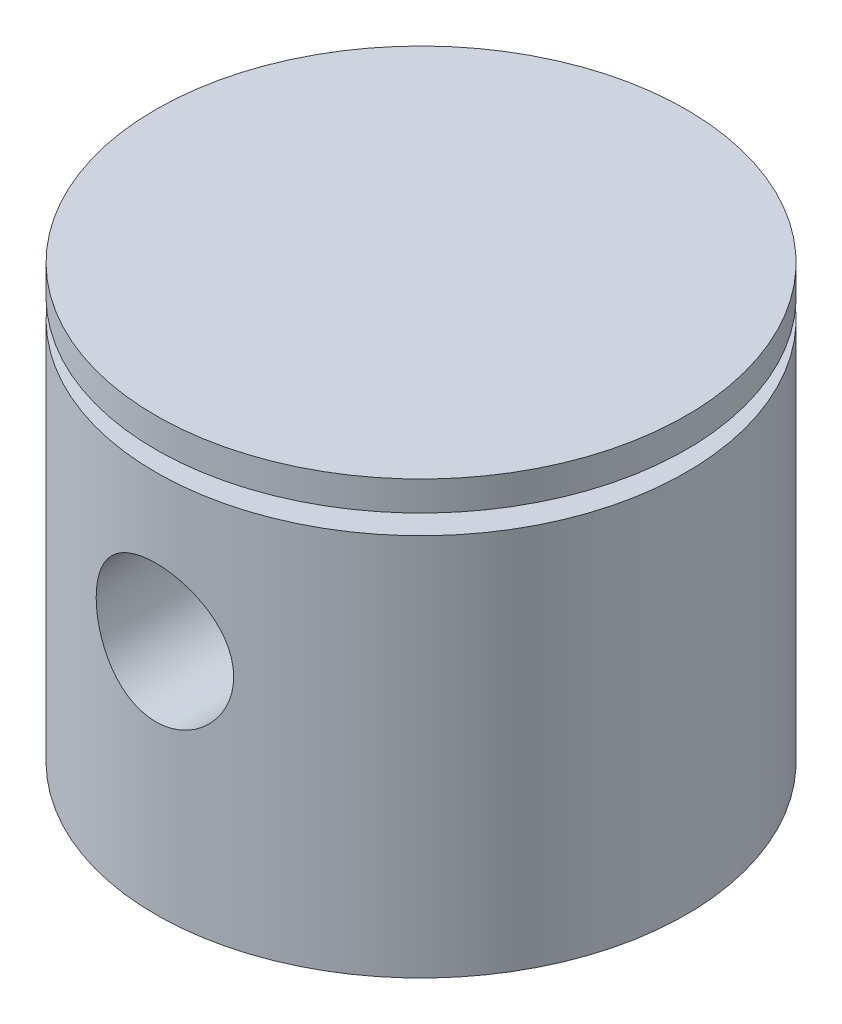
SolidWorks part; units mm, degrees
ref_plane "Plan de face" through (0, 0, 0) normal (0, 0, 1) x (1, 0, 0)
ref_plane "Plan de dessus" through (0, 0, 0) normal (0, 1, 0) x (1, 0, 0)
ref_plane "Plan de droite" through (0, 0, 0) normal (1, 0, 0) x (0, 0, -1)
sketch "Esquisse11" plane through (0, 0, 0) normal (0, 0, 1) x (1, 0, 0)
  line L0 (0, 0) -> (-13.5, 0)
  line L1 (0, 0) -> (0, -3)
  line L2 (0, -3) -> (-7, -3)
  line L3 (-7, -3) -> (-7, -16)
  line L4 (-7, -16) -> (-12, -16)
  line L5 (-12, -16) -> (-12, -22)
  line L6 (-12, -22) -> (-13.5, -22)
  line L8 (-13.5, -22) -> (-13.5, -2.5)
  line L9 (-13.5, -2.5) -> (-11.5, -2.5)
  line L10 (-11.5, -2.5) -> (-11.5, -1.5)
  line L11 (-11.5, -1.5) -> (-13.5, -1.5)
  line L12 (-13.5, -1.5) -> (-13.5, 0)
  line L13 (0, 0) -> (0, -22) construction
  point P8 (0, 0)
  point P15 (-16.1766, -2.3018)
  point P16 (0, 0)
  point P17 (0, 0)
  point P18 (0, 0)
  point P19 (0, 0)
  point P20 (-13.5, -1.5121)
  dimension "D1" = 13.5
  dimension "D2" = 3
  dimension "D3" = 7
  dimension "D4" = 13
  dimension "D5" = 5
  dimension "D6" = 6
  dimension "D7" = 1.5
  dimension "D8" = 1.5
  dimension "D9" = 2
  dimension "D10" = 1
revolve "Révolution5" add sketch "Esquisse11" angle 360 about L13
sketch "Esquisse12" plane through (0, 0, 0) normal (0, 0, 1) x (1, 0, 0)
  line L0 (0, 0) -> (0, -20) construction
  line L1 (0, 0) -> (0, -10)
  circle A0 centre (0, -10) radius 3.5
  dimension "D2" = 7
  dimension "D1" = 10
extrude "Enlèv. mat.-Extru.3" cut sketch "Esquisse12" against normal through all both and the other way through all contours A0
